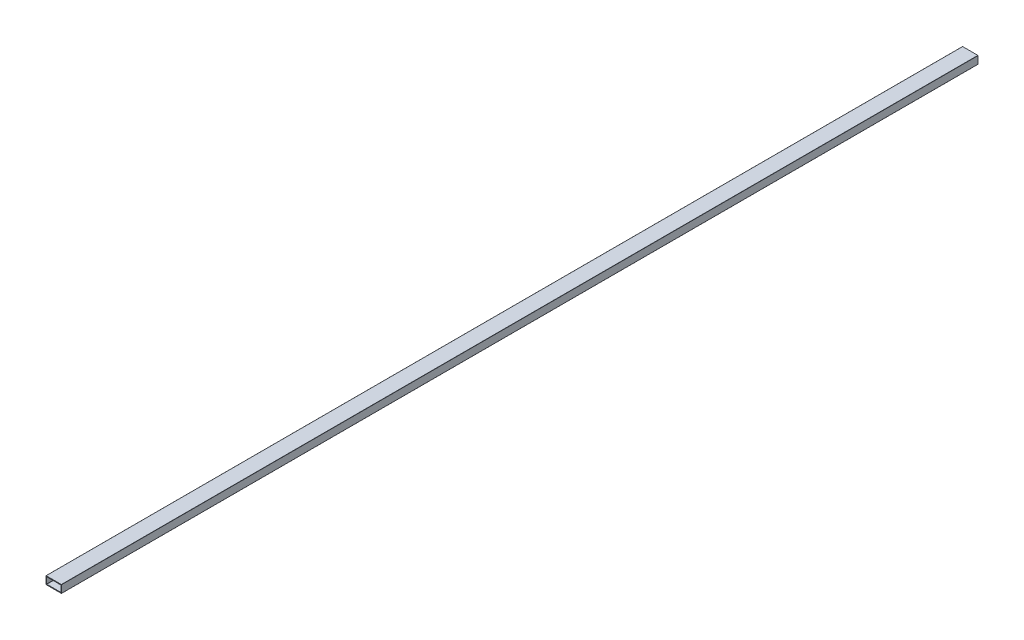
SolidWorks part; units mm, degrees
material "AISI 1035 Acero (SS)"
ref_plane "Alzado" through (0, 0, 0) normal (0, 0, 1) x (1, 0, 0)
ref_plane "Planta" through (0, 0, 0) normal (0, 1, 0) x (1, 0, 0)
ref_plane "Vista lateral" through (0, 0, 0) normal (1, 0, 0) x (0, 0, -1)
sketch "Croquis1" plane through (0, 0, 0) normal (0, 0, 1) x (1, 0, 0)
  line L0 (-46.25, -20.85) -> (-46.25, 20.85)
  line L1 (-50.8, -25.4) -> (50.8, -25.4)
  line L2 (-50.8, -25.4) -> (-50.8, 25.4)
  line L3 (-50.8, 25.4) -> (50.8, 25.4)
  line L4 (50.8, -25.4) -> (50.8, 25.4)
  line L5 (-50.8, -25.4) -> (50.8, 25.4) construction
  line L6 (-50.8, 25.4) -> (50.8, -25.4) construction
  line L7 (-46.25, 20.85) -> (46.25, 20.85)
  line L8 (46.25, -20.85) -> (46.25, 20.85)
  line L9 (-46.25, -20.85) -> (46.25, -20.85)
  point P0 (0, 0)
  dimension "D1" = 50.8
  dimension "D2" = 101.6
  dimension "D3" = 4.55
extrude "Saliente-Extruir1" add sketch "Croquis1" against normal blind 6000
fillet "Redondeo1" radius 1 8 edges at (-46.25, 20.85, -3000) (46.25, 20.85, -3000) (46.25, -20.85, -3000) (-50.8, -25.4, -3000) (-50.8, 25.4, -3000) (-46.25, -20.85, -3000) (50.8, -25.4, -3000) (50.8, 25.4, -3000)
